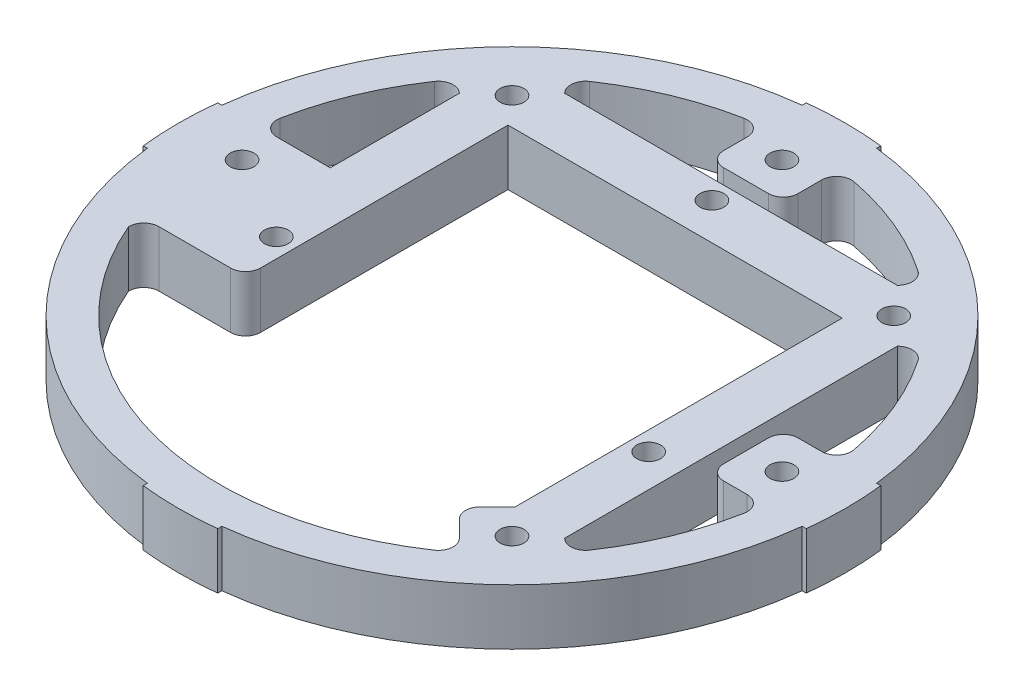
SolidWorks part; units mm, degrees
ref_plane "Front Plane" through (0, 0, 0) normal (0, 0, 1) x (1, 0, 0)
ref_plane "Top Plane" through (0, 0, 0) normal (0, 1, 0) x (1, 0, 0)
ref_plane "Right Plane" through (0, 0, 0) normal (1, 0, 0) x (0, 0, -1)
sketch "Sketch2" plane through (0, 0, 0) normal (0, 1, 0) x (1, 0, 0)
  line L0 (0, 0) -> (52.9832, 0) construction
  line L1 (31.43, 3) -> (31.43, -3)
  line L2 (33.43, 5) -> (45.2963, 5) construction
  line L3 (33.43, 5) -> (36.5861, 5)
  line L4 (45.2963, -5) -> (33.43, -5) construction
  line L5 (33.43, -5) -> (36.5861, -5)
  line L6 (27.1741, -20.103) -> (35.5648, -28.4938) construction
  line L7 (27.1741, -20.103) -> (29.4058, -22.3348)
  line L8 (24.3457, -20.103) -> (20.103, -24.3457)
  line L9 (20.103, -27.1741) -> (22.3348, -29.4058)
  line L10 (28.4938, -35.5648) -> (20.103, -27.1741) construction
  line L16 (-20.103, -27.1741) -> (-28.4938, -35.5648) construction
  line L20 (-35.5648, -28.4938) -> (-27.1741, -20.103) construction
  line L21 (-33.43, -5) -> (-45.2963, -5) construction
  line L22 (-33.43, -5) -> (-36.5861, -5)
  line L23 (-31.43, -3) -> (-31.43, 3)
  line L24 (-33.43, 5) -> (-36.5861, 5)
  line L25 (-45.2963, 5) -> (-33.43, 5) construction
  line L26 (-27.1741, 20.103) -> (-35.5648, 28.4938) construction
  line L27 (-27.1741, 20.103) -> (-29.4058, 22.3348)
  line L28 (-24.3457, 20.103) -> (-20.103, 24.3457)
  line L29 (-20.103, 27.1741) -> (-22.3348, 29.4058)
  line L30 (-28.4938, 35.5648) -> (-20.103, 27.1741) construction
  line L31 (-5, 33.43) -> (-5, 45.2963) construction
  line L32 (-5, 33.43) -> (-5, 36.5861)
  line L33 (-3, 31.43) -> (3, 31.43)
  line L34 (5, 33.43) -> (5, 36.5861)
  line L35 (5, 45.2963) -> (5, 33.43) construction
  line L36 (20.103, 27.1741) -> (28.4938, 35.5648) construction
  line L37 (20.103, 27.1741) -> (22.3348, 29.4058)
  line L38 (20.103, 24.3457) -> (24.3457, 20.103)
  line L39 (27.1741, 20.103) -> (29.4058, 22.3348)
  line L40 (35.5648, 28.4938) -> (27.1741, 20.103) construction
  line L41 (43.9666, 5) -> (44.5201, 5)
  line L42 (43.9666, -5) -> (44.5201, -5)
  line L43 (-5, -43.9666) -> (-5, -44.5201)
  line L44 (5, -43.9666) -> (5, -44.5201)
  line L45 (-43.9666, 5) -> (-44.5201, 5)
  line L46 (-43.9666, -5) -> (-44.5201, -5)
  line L47 (5, 43.9666) -> (5, 44.5201)
  line L48 (-5, 43.9666) -> (-5, 44.5201)
  line L49 (3, -31.43) -> (-3, -31.43) [skipped]
  line L50 (-5, -33.43) -> (-5, -36.5861) [skipped]
  line L51 (5, -33.43) -> (5, -36.5861) [skipped]
  line L52 (5, -33.43) -> (5, -45.2963) construction
  line L53 (-5, -45.2963) -> (-5, -33.43) construction
  line L54 (-20.103, -24.3457) -> (-24.3457, -20.103) [skipped]
  line L55 (-20.103, -27.1741) -> (-22.3348, -29.4058) [skipped]
  line L56 (-27.1741, -20.103) -> (-29.4058, -22.3348) [skipped]
  circle A0 centre (0, 0) radius 44.25 construction
  circle A1 centre (0, 0) radius 39.25 construction
  circle A2 centre (0, 0) radius 36.25 construction
  circle A3 centre (36.25, 0) radius 1.6
  arc A4 (31.43, 3) -> (33.43, 5) centre (33.43, 3) cw
  arc A5 (31.43, -3) -> (33.43, -5) centre (33.43, -3) ccw
  arc A6 (36.5861, 5) -> (38.5507, 7.3758) centre (36.5864, 7) ccw
  arc A7 (36.5861, -5) -> (38.5507, -7.3758) centre (36.5864, -7) cw
  arc A8 (29.4058, -22.3348) -> (32.475, -22.044) centre (30.8202, -20.9207) ccw
  arc A9 (24.3457, -20.103) -> (27.1741, -20.103) centre (25.7599, -21.5173) cw
  arc A10 (20.103, -24.3457) -> (20.103, -27.1741) centre (21.5173, -25.7599) ccw
  arc A11 (22.3348, -29.4058) -> (22.044, -32.475) centre (20.9207, -30.8202) cw
  circle A12 centre (25.6326, -25.6326) radius 1.6
  arc A13 (-38.5507, -7.3758) -> (22.044, -32.475) centre (0, 0) ccw
  arc A23 (-36.5861, -5) -> (-38.5507, -7.3758) centre (-36.5864, -7) ccw
  arc A24 (-31.43, -3) -> (-33.43, -5) centre (-33.43, -3) cw
  arc A25 (-31.43, 3) -> (-33.43, 5) centre (-33.43, 3) ccw
  arc A26 (-36.5861, 5) -> (-38.5507, 7.3758) centre (-36.5864, 7) cw
  circle A27 centre (-36.25, 0) radius 1.6
  arc A28 (-29.4058, 22.3348) -> (-32.475, 22.044) centre (-30.8202, 20.9207) ccw
  arc A29 (-24.3457, 20.103) -> (-27.1741, 20.103) centre (-25.7599, 21.5173) cw
  arc A30 (-20.103, 24.3457) -> (-20.103, 27.1741) centre (-21.5173, 25.7599) ccw
  arc A31 (-22.3348, 29.4058) -> (-22.044, 32.475) centre (-20.9207, 30.8202) cw
  circle A32 centre (-25.6326, 25.6326) radius 1.6
  arc A33 (-5, 36.5861) -> (-7.3758, 38.5507) centre (-7, 36.5864) ccw
  arc A34 (-3, 31.43) -> (-5, 33.43) centre (-3, 33.43) cw
  arc A35 (3, 31.43) -> (5, 33.43) centre (3, 33.43) ccw
  arc A36 (5, 36.5861) -> (7.3758, 38.5507) centre (7, 36.5864) cw
  circle A37 centre (0, 36.25) radius 1.6
  arc A38 (22.3348, 29.4058) -> (22.044, 32.475) centre (20.9207, 30.8202) ccw
  arc A39 (20.103, 24.3457) -> (20.103, 27.1741) centre (21.5173, 25.7599) cw
  arc A40 (24.3457, 20.103) -> (27.1741, 20.103) centre (25.7599, 21.5173) ccw
  arc A41 (29.4058, 22.3348) -> (32.475, 22.044) centre (30.8202, 20.9207) cw
  circle A42 centre (25.6326, 25.6326) radius 1.6
  arc A43 (32.475, 22.044) -> (38.5507, 7.3758) centre (0, 0) cw
  arc A44 (38.5507, -7.3758) -> (32.475, -22.044) centre (0, 0) cw
  arc A48 (-38.5507, 7.3758) -> (-32.475, 22.044) centre (0, 0) cw
  arc A49 (-22.044, 32.475) -> (-7.3758, 38.5507) centre (0, 0) cw
  arc A50 (7.3758, 38.5507) -> (22.044, 32.475) centre (0, 0) cw
  arc A51 (44.5201, 5) -> (44.5201, -5) centre (0, 0) cw
  arc A52 (5, -44.5201) -> (-5, -44.5201) centre (0, 0) cw
  arc A53 (-44.5201, -5) -> (-44.5201, 5) centre (0, 0) cw
  arc A54 (-5, 44.5201) -> (5, 44.5201) centre (0, 0) cw
  arc A55 (5, 43.9666) -> (43.9666, 5) centre (0, 0) cw
  arc A56 (43.9666, -5) -> (5, -43.9666) centre (0, 0) cw
  arc A57 (-5, -43.9666) -> (-43.9666, -5) centre (0, 0) cw
  arc A58 (-43.9666, 5) -> (-5, 43.9666) centre (0, 0) cw
  arc A59 (5, -36.5861) -> (7.3758, -38.5507) centre (7, -36.5864) ccw [skipped]
  arc A60 (-5, -36.5861) -> (-7.3758, -38.5507) centre (-7, -36.5864) cw [skipped]
  arc A61 (3, -31.43) -> (5, -33.43) centre (3, -33.43) cw [skipped]
  arc A62 (-3, -31.43) -> (-5, -33.43) centre (-3, -33.43) ccw [skipped]
  circle A63 centre (0, -36.25) radius 1.6 [skipped]
  arc A64 (-24.3457, -20.103) -> (-27.1741, -20.103) centre (-25.7599, -21.5173) ccw [skipped]
  arc A65 (-20.103, -24.3457) -> (-20.103, -27.1741) centre (-21.5173, -25.7599) cw [skipped]
  arc A66 (-22.3348, -29.4058) -> (-22.044, -32.475) centre (-20.9207, -30.8202) ccw [skipped]
  circle A67 centre (-25.6326, -25.6326) radius 1.6 [skipped]
  arc A68 (-29.4058, -22.3348) -> (-32.475, -22.044) centre (-30.8202, -20.9207) cw [skipped]
  arc A69 (-7.3758, -38.5507) -> (-22.044, -32.475) centre (0, 0) cw [skipped]
  arc A70 (22.044, -32.475) -> (7.3758, -38.5507) centre (0, 0) cw [skipped]
  arc A71 (-32.475, -22.044) -> (-38.5507, -7.3758) centre (0, 0) cw [skipped]
  point P17 (39.25, 0)
  point P22 (43.9666, 5)
  point P25 (43.9666, -5)
  point P26 (31.43, 0)
  point P43 (22.2244, -22.2244)
  point P47 (0, -31.43)
  point P77 (-22.2244, -22.2244)
  point P94 (-31.43, 0)
  point P111 (-22.2244, 22.2244)
  point P128 (0, 31.43)
  point P145 (22.2244, 22.2244)
  point P146 (0, 0)
  point P147 (0, 0)
  point P163 (0, 0)
  point P172 (0, 0)
  point P176 (0, 0)
  dimension "D1" = 5
  dimension "D3" = 10
  dimension "D2" = 3
  dimension "D5" = 7.82
  dimension "D6" = 8
  dimension "D4" = 4.82
  dimension "D8" = 4
  dimension "D7" = 8
  dimension "D9" = 4
extrude "Boss-Extrude2" add sketch "Sketch2" along normal blind 7.5
sketch "Sketch3" plane through (0, 0, 0) normal (0, -1, 0) x (1, 0, 0)
  line L0 (0, -21.902) -> (0, -26.8477) construction
  line L1 (22.4409, -21.902) -> (-22.4409, -21.902)
  line L2 (22.4409, -21.902) -> (22.4409, 24.0326)
  line L3 (22, 37.15) -> (-22, 37.15) construction
  line L4 (-22.4409, -21.902) -> (-22.4409, 6.65)
  line L5 (-22.4409, 6.65) -> (-25, 6.65) construction
  line L6 (22, 6.65) -> (25, 6.65) construction
  line L7 (22, 37.15) -> (22, 44.25) construction
  line L8 (22, 44.25) -> (-22, 44.25) construction
  line L9 (-22, 44.25) -> (-22, 37.15) construction
  line L10 (0, 44.25) -> (0, 6.66) construction
  line L11 (22.3348, -29.4058) -> (-22.3348, -29.4058)
  line L12 (-29.4058, -22.3348) -> (-29.4058, -5)
  line L13 (-33.43, -5) -> (-29.4058, -5)
  line L14 (29.4058, -22.3348) -> (29.4058, 22.3348)
  line L15 (-22.4409, 6.65) -> (-22.4409, 11.3413)
  line L16 (29.4058, 29.4058) -> (23.4346, 29.4058)
  line L17 (29.4058, -22.3348) -> (29.4058, -29.4058)
  line L18 (29.4058, -29.4058) -> (22.3348, -29.4058)
  line L19 (29.4058, 29.4058) -> (29.4058, 22.3348)
  line L20 (-22.3348, -29.4058) -> (-29.4058, -29.4058)
  line L21 (-29.4058, -29.4058) -> (-29.4058, -22.3348)
  line L22 (-24.4409, 13.3413) -> (-29.4058, 13.3413)
  line L23 (23.4346, 29.4058) -> (23.4346, 25.6326)
  line L24 (23.4346, 25.6326) -> (22.4409, 25.6326)
  line L25 (-36.0914, 15.4263) -> (-39.5795, 15.4263)
  line L26 (-34.0914, 13.3413) -> (-29.4058, 13.3413)
  line L27 (22.4409, 25.6326) -> (22.4409, 24.0326)
  line L28 (-39.5795, 15.4263) -> (-39.5795, 13.3413)
  line L29 (-39.5795, 13.3413) -> (-39.5795, 3.4055)
  line L30 (-39.5795, 3.4055) -> (-33.43, 3.4055)
  line L31 (-33.43, -5) -> (-33.43, 3.4055)
  circle A0 centre (0, -26.8477) radius 1.6
  circle A1 centre (-25, 6.65) radius 1.6
  circle A2 centre (25, 6.65) radius 1.6
  arc A3 (22, 37.15) -> (-22, 37.15) centre (0, 6.66) ccw construction
  arc A4 (-22.4409, 11.3413) -> (-24.4409, 13.3413) centre (-24.4409, 11.3413) ccw
  circle A5 centre (25.6326, 25.6326) radius 1.6
  arc A6 (-34.0914, 13.3413) -> (-36.0914, 15.4263) centre (-34.0932, 15.3413) cw
  circle A8 centre (-25.6326, -25.6326) radius 1.6
  circle A9 centre (25.6326, -25.6326) radius 1.6
  arc A10 (22.044, 32.475) -> (-38.5507, 7.3758) centre (0, 0) ccw construction
  point P3 (0, -21.902)
  point P33 (25.6326, 25.6326)
  dimension "D4" = 28.552
extrude "Boss-Extrude3" add sketch "Sketch3" against normal blind 7.5
